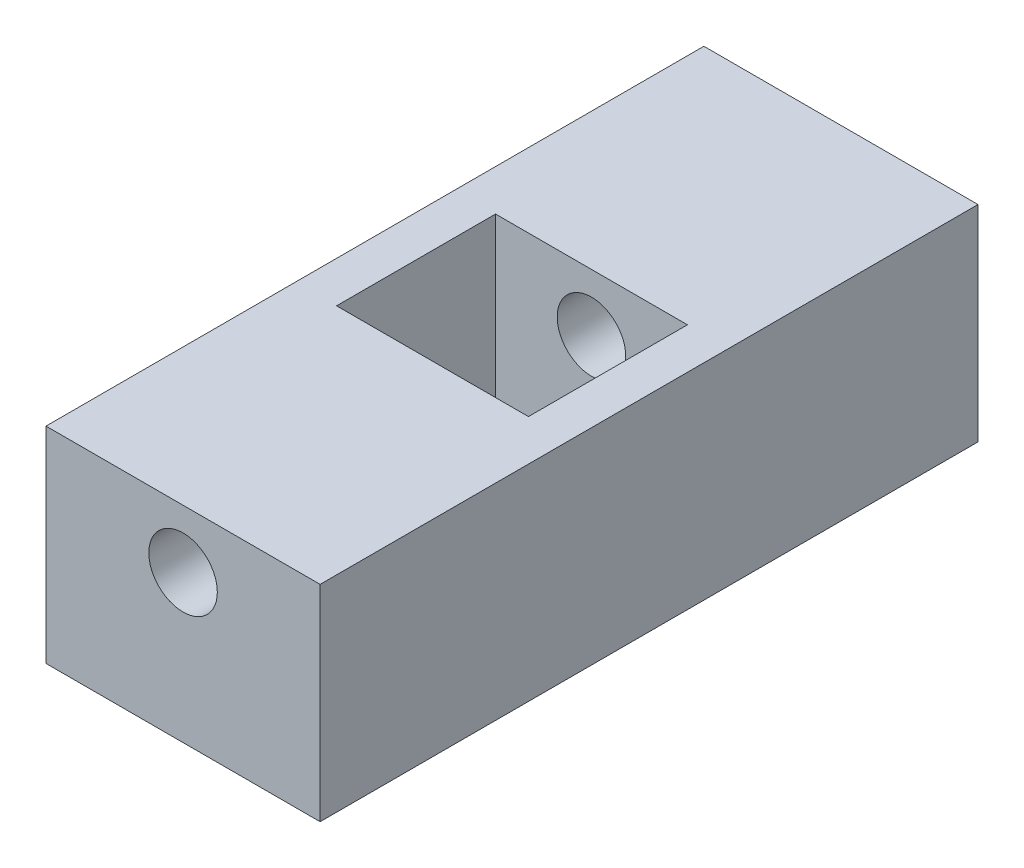
SolidWorks part; units mm, degrees
ref_plane "Front Plane" through (0, 0, 0) normal (0, 0, 1) x (1, 0, 0)
ref_plane "Top Plane" through (0, 0, 0) normal (0, 1, 0) x (1, 0, 0)
ref_plane "Right Plane" through (0, 0, 0) normal (1, 0, 0) x (0, 0, -1)
sketch "Sketch1" plane through (0, 0, 0) normal (0, 1, 0) x (1, 0, 0)
  line L13 (0, 0) -> (25.4, 0)
  line L14 (0, 0) -> (0, 60.96)
  line L15 (0, 60.96) -> (25.4, 60.96)
  line L16 (25.4, 0) -> (25.4, 60.96)
  dimension "D1" = 60.96
  dimension "D2" = 25.4
extrude "Boss-Extrude1" add sketch "Sketch1" along normal blind 19.05 contours L14 L15 L16 L13
sketch "Sketch3" plane through (0, 19.05, 0) normal (0, 1, 0) x (1, 0, 0)
  line L1 (3.81, 37.846) -> (21.59, 37.846)
  line L2 (3.81, 37.846) -> (3.81, 23.114)
  line L3 (3.81, 23.114) -> (21.59, 23.114)
  line L4 (21.59, 37.846) -> (21.59, 23.114)
  line L8 (0, 0) -> (25.4, 0)
  line L9 (25.4, 0) -> (25.4, 60.96)
  line L10 (25.4, 60.96) -> (0, 60.96)
  line L11 (0, 60.96) -> (0, 0)
  line L12 (0, 0) -> (25.4, 0) construction
  line L13 (25.4, 0) -> (25.4, 60.96) construction
  line L14 (25.4, 60.96) -> (0, 60.96) construction
  line L15 (0, 60.96) -> (0, 0) construction
  point P6 (25.4, 30.48)
  point P8 (21.59, 30.48)
  point P10 (12.7, 37.846)
  point P11 (12.7, 60.96)
  dimension "D1" = 14.732
  dimension "D2" = 17.78
  dimension "D3" = 0
extrude "Cut-Extrude1" cut sketch "Sketch3" against normal blind 19.05
sketch "Sketch5" plane through (0, 0, 0) normal (0, 0, 1) x (1, 0, 0)
  line L4 (0, 0) -> (25.4, 0)
  line L5 (25.4, 0) -> (25.4, 19.05)
  line L6 (25.4, 19.05) -> (0, 19.05)
  line L7 (0, 19.05) -> (0, 0)
  line L8 (0, 0) -> (25.4, 0) construction
  line L9 (25.4, 0) -> (25.4, 19.05) construction
  line L10 (25.4, 19.05) -> (0, 19.05) construction
  line L11 (0, 19.05) -> (0, 0) construction
  circle A0 centre (12.7, 13.6525) radius 3.175
  dimension "D1" = 6.35
  dimension "D4" = 5.3975
  dimension "D3" = 12.7
  dimension "D2" = 0
extrude "Cut-Extrude3" cut sketch "Sketch5" against normal blind 58.42
